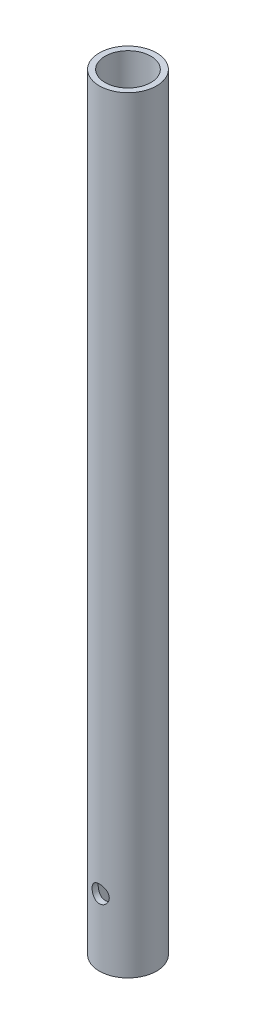
SolidWorks part; units mm, degrees
ref_plane "前视基准面" through (0, 0, 0) normal (0, 0, 1) x (1, 0, 0)
ref_plane "上视基准面" through (0, 0, 0) normal (0, 1, 0) x (1, 0, 0)
ref_plane "右视基准面" through (0, 0, 0) normal (1, 0, 0) x (0, 0, -1)
sketch "草图1" plane through (0, 0, 0) normal (0, 1, 0) x (1, 0, 0)
  circle A0 centre (0, 0) radius 20
  circle A1 centre (0, 0) radius 25
  dimension "D1" = 40
  dimension "D2" = 50
extrude "凸台-拉伸1" add sketch "草图1" along normal blind 670
extrude "切除-拉伸3" cut sketch "草图4" against normal mid plane 50
sketch "草图4" plane through (0, 0, 0) normal (0, 0, 1) x (1, 0, 0)
  circle A0 centre (0, 58.5165) radius 7.5
